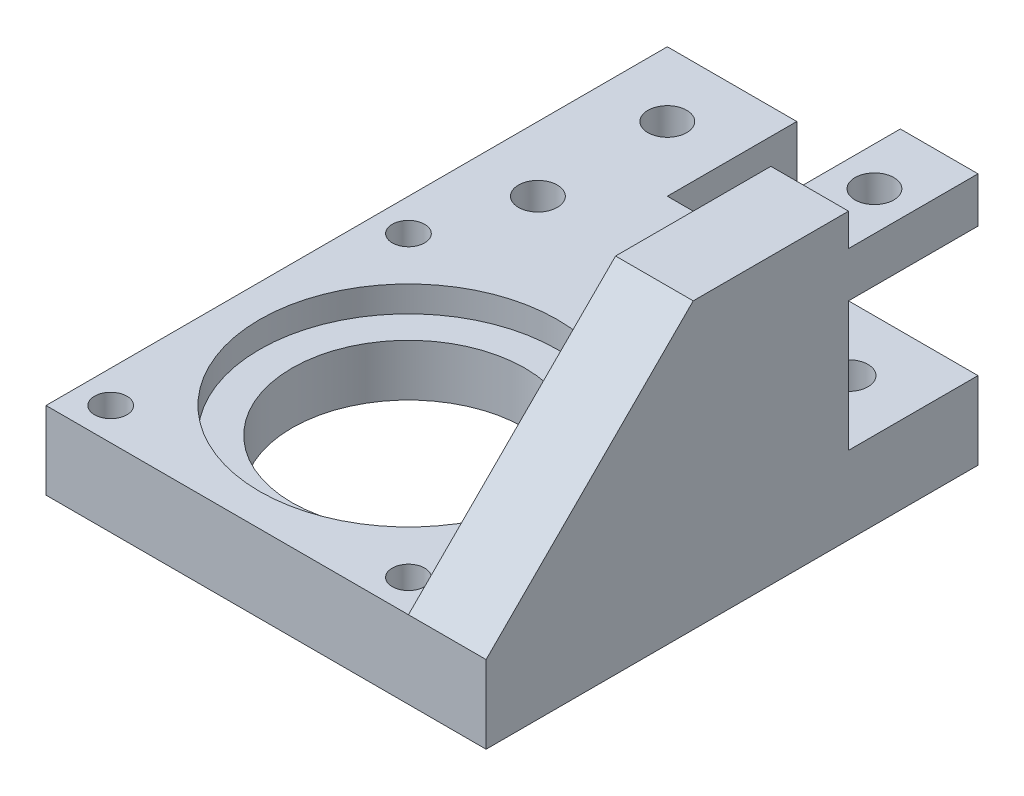
SolidWorks part; units mm, degrees
ref_plane "Front Plane" through (0, 0, 0) normal (0, 0, 1) x (1, 0, 0)
ref_plane "Top Plane" through (0, 0, 0) normal (0, 1, 0) x (1, 0, 0)
ref_plane "Right Plane" through (0, 0, 0) normal (1, 0, 0) x (0, 0, -1)
sketch "Sketch2" plane through (0, 0, 0) normal (0, 1, 0) x (1, 0, 0)
  line L0 (11, -5) -> (-17, -5) construction
  line L1 (-17, -19) -> (17, -19)
  line L2 (-17, -19) -> (-17, 19)
  line L3 (-17, 19) -> (17, 19)
  line L4 (17, -19) -> (17, 19)
  line L5 (-17, -19) -> (17, 19) construction
  line L6 (-17, 19) -> (17, -19) construction
  line L7 (17, -19) -> (11, -19)
  line L8 (17, -19) -> (17, 6.9764)
  line L9 (17, 6.9764) -> (11, 6.9764)
  line L10 (11, -19) -> (11, 6.9764)
  circle A0 centre (-3, -5) radius 9
  point P0 (0, 0)
  point P8 (0, 0)
  point P14 (0, 0)
  point P15 (-3, -5)
  dimension "D3" = 18
  dimension "D1" = 34
  dimension "D2" = 38
  dimension "D4" = 14
  dimension "D5" = 28
extrude "Boss-Extrude1" add sketch "Sketch2" along normal blind 6 contours L1 L10 L9 L4 L3 L2 A0 | L10 L1 L4 L9
sketch "Sketch3" plane through (0, 0, -19) normal (0, 0, -1) x (-1, 0, 0)
  line L0 (17, 0) -> (-17, 0) construction
  line L1 (17, 6) -> (7, 6)
  line L2 (17, 6) -> (17, 0)
  line L3 (17, 0) -> (7, 0)
  line L4 (7, 6) -> (7, 0)
  dimension "D1" = 10
extrude "Boss-Extrude2" add sketch "Sketch3" along normal blind 10
sketch "Sketch4" plane through (0, 6, 0) normal (0, 1, 0) x (1, 0, 0)
  line L1 (17, -19) -> (11, -19)
  line L2 (17, -19) -> (17, 9)
  line L3 (17, 9) -> (11, 9)
  line L4 (11, -19) -> (11, 9)
  dimension "D1" = 28
  dimension "D2" = 6
extrude "Boss-Extrude3" add sketch "Sketch4" along normal blind 16
chamfer "Chamfer1" distance 16 angle 45 1 edges at (14, 22, 19)
sketch "Sketch5" plane through (0, 0, -9) normal (0, 0, -1) x (-1, 0, 0)
  line L0 (-17, 22) -> (-17, 6) construction
  line L1 (-11, 22) -> (-17, 22)
  line L2 (-11, 22) -> (-11, 16)
  line L3 (-11, 16) -> (-17, 16)
  line L4 (-17, 22) -> (-17, 16)
  line L5 (-17, 6) -> (-11, 6) construction
  line L6 (-11, 22) -> (-11, 6) construction
  point P9 (0, 0)
  point P10 (0, 0)
  point P12 (0, 0)
  point P13 (-11, 21.7694)
  point P14 (-11, 22)
  dimension "D1" = 10
extrude "Boss-Extrude4" add sketch "Sketch5" along normal up to surface (10 mm away) up to face at (5, 3, -19)
sketch "Sketch6" plane through (0, 22, 0) normal (0, -1, 0) x (1, 0, 0)
  line L0 (17, -9) -> (-17, -9) construction
  line L1 (-17, 19) -> (-17, -29) construction
  line L2 (14, -9) -> (14, -19) construction
  line L3 (11, -19) -> (17, -19) construction
  circle A0 centre (14, -14) radius 1.5
  point P2 (14, -14)
  dimension "D1" = 3
sketch "Sketch7" plane through (0, 0, 0) normal (0, -1, 0) x (1, 0, 0)
  line L0 (17, -9) -> (-17, -9) construction
  line L1 (0, -19) -> (0, -9) construction
  line L2 (-7, -19) -> (17, -19) construction
  line L3 (-7, -24) -> (-17, -24) construction
  line L4 (-7, -29) -> (-7, -19) construction
  line L5 (-17, 19) -> (-17, -29) construction
  circle A1 centre (0, -14) radius 1.5
  circle A2 centre (-12, -14) radius 1.5
  circle A3 centre (-12, -24) radius 1.5
  circle A4 centre (12, -14) radius 1.5
  point P0 (0, 0)
  point P8 (-12, -24)
  point P11 (0, -9)
  point P16 (0.5736, -14.1629)
  point P19 (0, -14)
  dimension "D1" = 3
extrude "Cut-Extrude1" cut sketch "Sketch7" against normal up to next
extrude "Cut-Extrude2" cut sketch "Sketch6" along normal up to next
sketch "Sketch9" plane through (0, 22, 0) normal (0, 1, 0) x (1, 0, 0)
  line L0 (11, 19) -> (11, -3) construction
  line L1 (17, 19) -> (11, 19)
  line L2 (17, 19) -> (17, 9)
  line L3 (17, 9) -> (11, 9)
  line L4 (11, 19) -> (11, 9)
  point P7 (0, 0)
  point P8 (0, 0)
extrude "Cut-Extrude3" cut sketch "Sketch9" against normal blind 2.5
sketch "Sketch10" plane through (0, 0, 0) normal (0, -1, 0) x (1, 0, 0)
  circle A0 centre (12, -14) radius 3
  circle A1 centre (0, -14) radius 3
  circle A2 centre (-12, -14) radius 3
  circle A3 centre (-12, -24) radius 3
  dimension "D1" = 6
extrude "Cut-Extrude4" cut sketch "Sketch10" against normal blind 2.5
sketch "Sketch11" plane through (0, 6, 0) normal (0, 1, 0) x (1, 0, 0)
  circle A0 centre (-3, -5) radius 11.5
  dimension "D1" = 23
extrude "Cut-Extrude5" cut sketch "Sketch11" against normal blind 2
sketch "Sketch13" plane through (0, 6, 0) normal (0, 1, 0) x (1, 0, 0)
  line L1 (-14.5, -16.5) -> (8.5, -16.5) construction
  line L2 (-14.5, -16.5) -> (-14.5, 6.5) construction
  line L3 (-14.5, 6.5) -> (8.5, 6.5) construction
  line L4 (8.5, -16.5) -> (8.5, 6.5) construction
  line L5 (-14.5, -16.5) -> (8.5, 6.5) construction
  line L6 (-14.5, 6.5) -> (8.5, -16.5) construction
  circle A0 centre (-14.5, 6.5) radius 1.25
  circle A1 centre (8.5, 6.5) radius 1.25
  circle A2 centre (8.5, -16.5) radius 1.25
  circle A3 centre (-14.5, -16.5) radius 1.25
  circle A4 centre (-3, -5) radius 11.5 construction
  point P0 (6.4123, -13.9606)
  point P8 (-3, -5)
  point P9 (-11.5421, 3.9606)
  dimension "D1" = 2.5
extrude "Cut-Extrude6" cut sketch "Sketch13" against normal up to next
